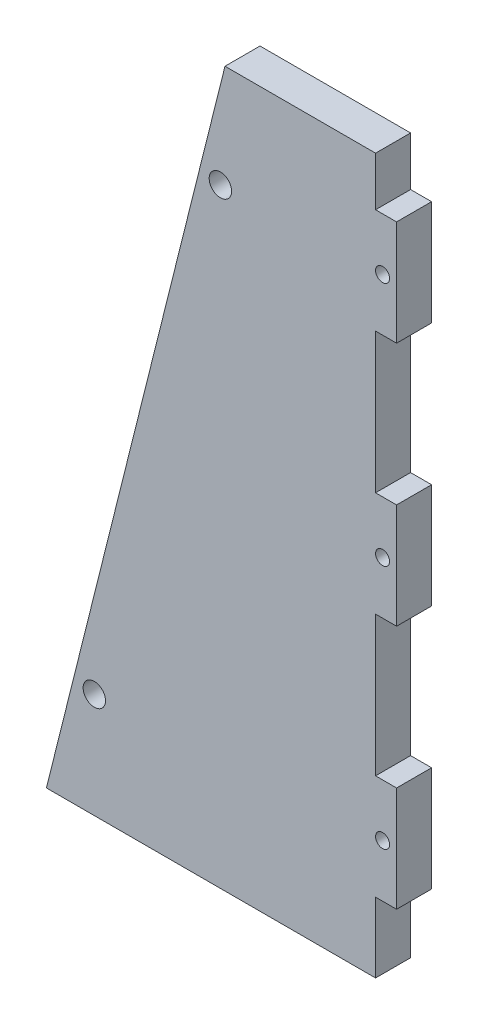
SolidWorks part; units mm, degrees
ref_plane "Front" through (0, 0, 0) normal (0, 0, 1) x (1, 0, 0)
ref_plane "Top" through (0, 0, 0) normal (0, 1, 0) x (1, 0, 0)
ref_plane "Right" through (0, 0, 0) normal (1, 0, 0) x (0, 0, -1)
sketch "草图1" plane through (0, 0, 0) normal (0, 0, 1) x (1, 0, 0)
  line L0 (0, 0) -> (0, 100)
  line L1 (0, 100) -> (-25, 100)
  line L2 (-25, 100) -> (-50, 0)
  line L3 (-50, 0) -> (0, 0)
  dimension "D1" = 25
  dimension "D2" = 50
  dimension "D3" = 100
extrude "凸台-拉伸1" add sketch "草图1" along normal blind 5
sketch "草图2" plane through (0, 0, 5) normal (0, 0, 1) x (1, 0, 0)
  line L0 (0, 0) -> (0, 100) construction
  line L1 (0, 0) -> (-3, 0)
  line L2 (0, 0) -> (0, 10)
  line L3 (0, 10) -> (-3, 10)
  line L4 (-3, 0) -> (-3, 10)
  line L5 (0, 25) -> (-3, 25)
  line L6 (0, 25) -> (0, 45)
  line L7 (0, 45) -> (-3, 45)
  line L8 (-3, 25) -> (-3, 45)
  line L10 (0, 60) -> (-3, 60)
  line L11 (0, 60) -> (0, 80)
  line L12 (0, 80) -> (-3, 80)
  line L13 (-3, 60) -> (-3, 80)
  line L14 (0, 95) -> (-3, 95)
  line L15 (0, 95) -> (0, 107.0224)
  line L16 (0, 107.0224) -> (-3, 107.0224)
  line L17 (-3, 95) -> (-3, 107.0224)
  dimension "D1" = 3
  dimension "D2" = 10
  dimension "D3" = 20
  dimension "D4" = 15
  dimension "D5" = 3
  dimension "D6" = 20
  dimension "D7" = 15
  dimension "D8" = 3
  dimension "D9" = 3
  dimension "D10" = 15
extrude "切除-拉伸1" cut sketch "草图2" against normal through all
sketch "草图3" plane through (0, 0, 5) normal (0, 0, 1) x (1, 0, 0)
  line L0 (-3, 100) -> (-3, 102)
  line L1 (-3, 100) -> (-25, 100)
  line L2 (-25, 100) -> (-24.5, 102)
  line L3 (-24.5, 102) -> (-3, 102)
  line L4 (-25, 100) -> (-50, 0) construction
  dimension "D12" = 2
  dimension "D2" = 180
extrude "凸台-拉伸2" add sketch "草图3" against normal blind 5
sketch "草图4" plane through (0, 0, 5) normal (0, 0, 1) x (1, 0, 0)
  line L0 (-3, 102) -> (-24.5, 102) construction
  line L1 (-24.5, 102) -> (-50, 0) construction
  line L2 (-50, 0) -> (-3, 0) construction
  circle A0 centre (-25.1577, 87) radius 1.6
  circle A1 centre (-43.1577, 15) radius 1.6
  dimension "D1" = 15
  dimension "D2" = 3
  dimension "D3" = 15
  dimension "D4" = 3
extrude "切除-拉伸2" cut sketch "草图4" against normal through all
sketch "草图5" plane through (0, 0, 5) normal (0, 0, 1) x (1, 0, 0)
  line L0 (0, 80) -> (0, 95) construction
  circle A0 centre (-2, 87.5) radius 1
  circle A1 centre (-2, 52.5) radius 1
  circle A2 centre (-2, 17.5) radius 1
  dimension "D1" = 2
extrude "切除-拉伸3" cut sketch "草图5" against normal through all
